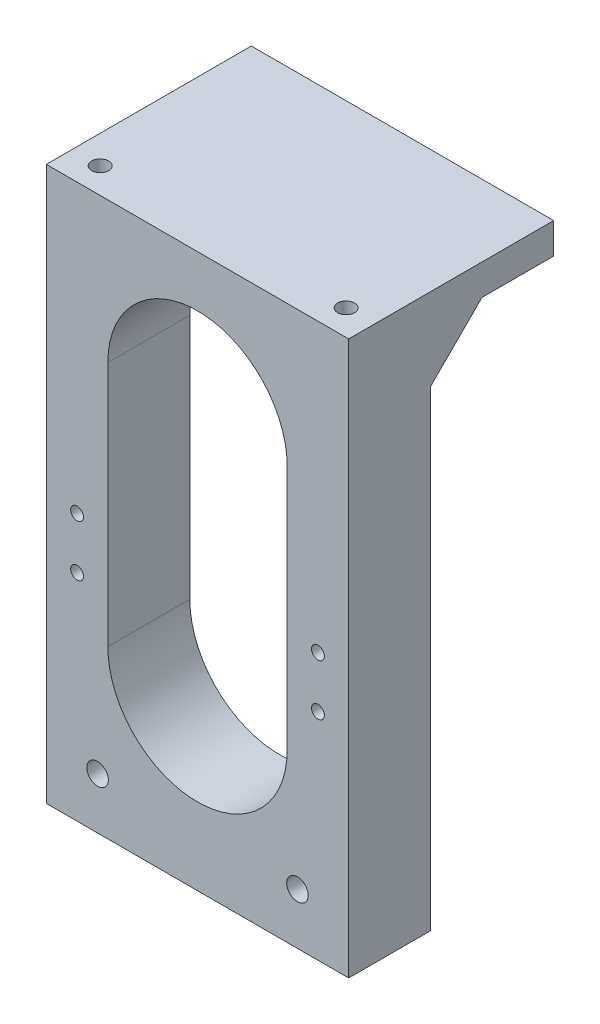
SolidWorks part; units mm, degrees
material "6061 合金"
ref_plane "前视基准面" through (0, 0, 0) normal (0, 0, 1) x (1, 0, 0)
ref_plane "上视基准面" through (0, 0, 0) normal (0, 1, 0) x (1, 0, 0)
ref_plane "右视基准面" through (0, 0, 0) normal (1, 0, 0) x (0, 0, -1)
sketch "草图5" plane through (0, 0, 0) normal (1, 0, 0) x (0, 0, -1)
  line L0 (26, 102) -> (40, 102)
  line L1 (0, 0) -> (0, 108)
  line L2 (0, 108) -> (40, 108)
  line L3 (16, 92) -> (26, 102)
  line L4 (16, 92) -> (16, 0)
  line L5 (0, 0) -> (16, 0)
  line L6 (40, 102) -> (40, 108)
  point P7 (16, 102)
  dimension "D1" = 108
  dimension "D2" = 40
  dimension "D3" = 16
  dimension "D4" = 6
extrude "凸台-拉伸2" add sketch "草图5" along normal mid plane 59
hole_wizard "M4 螺纹孔2" positions "草图7" profile "草图6" tap size "M4" standard "GB"
sketch "草图7" plane through (0, 108, 0) normal (0, 1, 0) x (1, 0, 0)
  line L0 (0, 0) -> (0, 32.3961) construction
  line L1 (29.5, 0) -> (-29.5, 0) construction
  point P0 (24, 5)
  point P2 (-24, 5)
  dimension "D1" = 48
  dimension "D2" = 5
cosmetic thread "孔螺蚊线5"
cosmetic thread "孔螺蚊线6"
sketch "草图6" plane through (24, 108, -5) normal (1, 0, 0) x (0, 0, 1)
  line L0 (0, 0) -> (0, 12.4914)
  line L1 (0, 12.4914) -> (1.65, 11.5)
  line L2 (1.65, 11.5) -> (1.65, 0)
  line L5 (1.65, 0) -> (0, 0)
  line L10 (0, 12.4914) -> (-1.65, 11.5) construction
  line L11 (0, -6.35) -> (0, 107.95) construction
  dimension "螺纹孔钻头直径" = 3.3
  dimension "螺纹孔钻头深度" = 11.5
  dimension "导头角度" = 118
sketch "草图8" plane through (0, 0, 0) normal (0, 0, 1) x (1, 0, 0)
  line L0 (0, 80.5) -> (0, 32.5) construction
  line L1 (17.5, 80.5) -> (17.5, 32.5)
  line L2 (-17.5, 80.5) -> (-17.5, 32.5)
  line L4 (29.5, 0) -> (-29.5, 0) construction
  line L6 (29.5, 108) -> (-29.5, 108) construction
  line L7 (29.5, 108) -> (29.5, 0) construction
  arc A0 (17.5, 80.5) -> (-17.5, 80.5) centre (0, 80.5) ccw
  arc A1 (-17.5, 32.5) -> (17.5, 32.5) centre (0, 32.5) ccw
  point P3 (0, 56.5)
  dimension "D2" = 10
  dimension "D1" = 15
  dimension "D3" = 12
extrude "切除-拉伸1" cut sketch "草图8" against normal through all
hole_wizard "M5 螺纹孔1" positions "草图10" profile "草图9" tap size "M5" standard "GB" end condition through all
sketch "草图10" plane through (0, 0, 0) normal (0, 0, 1) x (1, 0, 0)
  line L0 (0, 0) -> (0, 48.3577) construction
  line L2 (29.5, 108) -> (29.5, 0) construction
  line L3 (29.5, 0) -> (-29.5, 0) construction
  point P0 (-19.5, 10)
  point P2 (19.5, 10)
  dimension "D1" = 10
  dimension "D2" = 10
sketch "草图9" plane through (-19.5, 10, 0) normal (1, 0, 0) x (0, -1, 0)
  line L0 (0, 0) -> (0, 40)
  line L1 (0, 40) -> (2.1, 40)
  line L2 (2.1, 40) -> (2.1, 0)
  line L5 (2.1, 0) -> (0, 0)
  line L11 (0, -6.35) -> (0, 107.95) construction
  dimension "通孔螺纹孔钻头直径" = 4.2
  dimension "通孔螺纹孔钻头深度" = 40
cosmetic thread "孔螺蚊线7"
cosmetic thread "孔螺蚊线8"
hole_wizard "M3 螺纹孔1" positions "草图12" profile "草图11" tap size "M3" standard "GB"
sketch "草图12" plane through (0, 0, 0) normal (0, 0, 1) x (1, 0, 0)
  line L0 (0, 0) -> (0, 83.5611) construction
  line L3 (-23.5, 52) -> (23.5, 52) construction
  line L4 (-23.5, 52) -> (-23.5, 42) construction
  line L5 (-23.5, 42) -> (23.5, 42) construction
  line L6 (23.5, 52) -> (23.5, 42) construction
  line L7 (-23.5, 52) -> (23.5, 42) construction
  line L8 (-23.5, 42) -> (23.5, 52) construction
  line L9 (29.5, 108) -> (29.5, 0) construction
  line L10 (-42.5, 0) -> (42.5, 0) construction
  point P15 (23.5, 42)
  point P18 (-23.5, 52)
  point P19 (-23.5, 42)
  point P20 (23.5, 52)
  dimension "D1" = 6
  dimension "D2" = 10
  dimension "D3" = 42
cosmetic thread "孔螺蚊线9"
cosmetic thread "孔螺蚊线10"
cosmetic thread "孔螺蚊线11"
cosmetic thread "孔螺蚊线12"
sketch "草图11" plane through (23.5, 42, 0) normal (1, 0, 0) x (0, -1, 0)
  line L0 (0, 0) -> (0, 9.2511)
  line L1 (0, 9.2511) -> (1.25, 8.5)
  line L2 (1.25, 8.5) -> (1.25, 0)
  line L5 (1.25, 0) -> (0, 0)
  line L10 (0, 9.2511) -> (-1.25, 8.5) construction
  line L11 (0, -6.35) -> (0, 107.95) construction
  dimension "螺纹孔钻头直径" = 2.5
  dimension "螺纹孔钻头深度" = 8.5
  dimension "导头角度" = 118
hole_wizard "M4 螺纹孔3" positions "草图14" profile "草图13" tap size "M4" standard "GB"
sketch "草图14" plane through (0, 0, 0) normal (0, -1, 0) x (-1, 0, 0)
  line L0 (-29.5, 8) -> (0, 8) construction
  line L1 (-29.5, 0) -> (-29.5, 16) construction
  point P0 (0, 8)
sketch "草图13" plane through (0, 0, -8) normal (1, 0, 0) x (0, 0, -1)
  line L0 (0, 0) -> (0, 12.4914)
  line L1 (0, 12.4914) -> (1.65, 11.5)
  line L2 (1.65, 11.5) -> (1.65, 0)
  line L5 (1.65, 0) -> (0, 0)
  line L10 (0, 12.4914) -> (-1.65, 11.5) construction
  line L11 (0, -6.35) -> (0, 107.95) construction
  dimension "螺纹孔钻头直径" = 3.3
  dimension "螺纹孔钻头深度" = 11.5
  dimension "导头角度" = 118
cosmetic thread "孔螺蚊线13" parameters "D1"=8, "D2"=4
